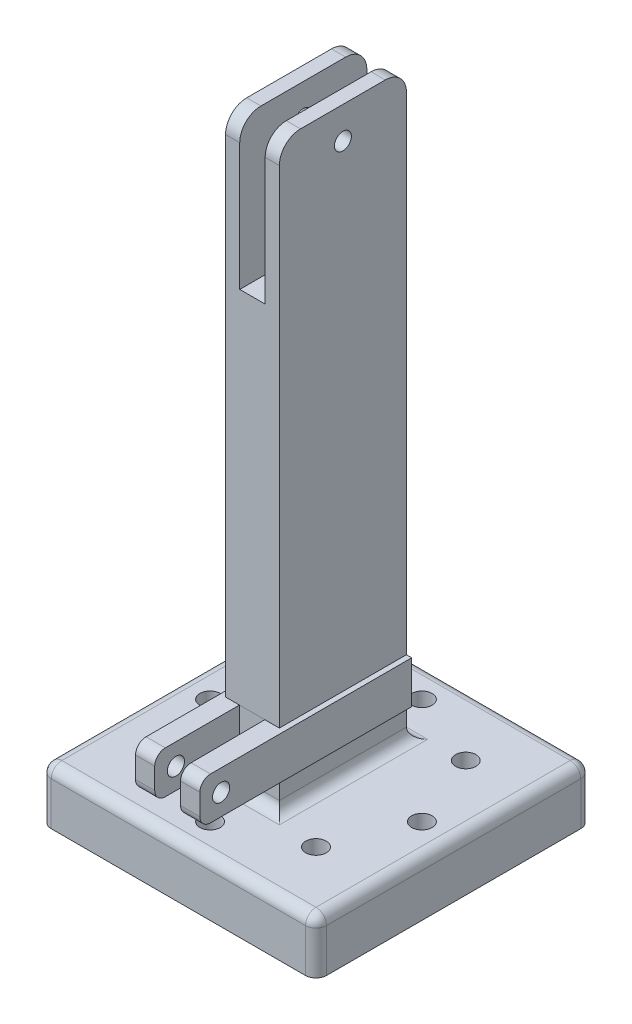
SolidWorks part; units mm, degrees
material "ABS P400"
ref_plane "Front Plane" through (0, 0, 0) normal (0, 0, 1) x (1, 0, 0)
ref_plane "Top Plane" through (0, 0, 0) normal (0, 1, 0) x (1, 0, 0)
ref_plane "Right Plane" through (0, 0, 0) normal (1, 0, 0) x (0, 0, -1)
sketch "Sketch1" plane through (0, 0, 0) normal (0, 1, 0) x (1, 0, 0)
  line L1 (32.5, -32.5) -> (-32.5, -32.5)
  line L2 (32.5, -32.5) -> (32.5, 32.5)
  line L3 (32.5, 32.5) -> (-32.5, 32.5)
  line L4 (-32.5, -32.5) -> (-32.5, 32.5)
  line L5 (32.5, -32.5) -> (-32.5, 32.5) construction
  line L6 (32.5, 32.5) -> (-32.5, -32.5) construction
  point P0 (0, 0)
  dimension "D1" = 65
extrude "Boss-Extrude1" add sketch "Sketch1" along normal blind 12.7
sketch "Sketch2" plane through (0, 0, 0) normal (1, 0, 0) x (0, 0, -1)
  line L0 (0, 0) -> (0, -27.9366) construction
  line L1 (-15, 0) -> (15, 0)
  line L3 (15, 0) -> (15, 145)
  line L4 (-10, 150) -> (10, 150)
  line L5 (-32.5, 0) -> (32.5, 0) construction
  line L6 (-15, 0) -> (-15, 145)
  arc A0 (15, 145) -> (10, 150) centre (10, 145) ccw
  arc A1 (-15, 145) -> (-10, 150) centre (-10, 145) cw
  circle A2 centre (0, 142.5) radius 2
  point P11 (15, 150)
  point P14 (-15, 150)
  dimension "D3" = 5
  dimension "D4" = 4
  dimension "D5" = 142.5
  dimension "D1" = 30
  dimension "D2" = 150
extrude "Boss-Extrude2" add sketch "Sketch2" along normal mid plane 12.7
fillet "Fillet1" radius 2.5 12 edges at (0, 12.7, -32.5) (32.5, 12.7, 0) (32.5, 6.35, -32.5) (32.5, 6.35, 32.5) (-32.5, 6.35, 32.5) (0, 12.7, 32.5) (-32.5, 6.35, -32.5) (-32.5, 12.7, 0) (0, 12.7, 15) (-6.35, 12.7, 0) (0, 12.7, -15) (6.35, 12.7, 0)
sketch "Sketch3" plane through (0, 0, 0) normal (0, 1, 0) x (1, 0, 0)
  line L0 (0, 158.75) -> (0, -158.75) construction
  line L1 (17.6777, 17.6777) -> (-17.6777, -17.6777) construction
  line L2 (17.6777, -17.6777) -> (-17.6777, 17.6777) construction
  circle A0 centre (0, 0) radius 25
  circle A1 centre (17.6777, -17.6777) radius 2.413
  circle A2 centre (25, 0) radius 2.413
  circle A3 centre (17.6777, 17.6777) radius 2.413
  circle A4 centre (0, 25) radius 2.413
  circle A5 centre (-17.6777, 17.6777) radius 2.413
  circle A6 centre (-25, 0) radius 2.413
  circle A7 centre (-17.6777, -17.6777) radius 2.413
  circle A8 centre (0, -25) radius 2.413
extrude "Cut-Extrude2" cut sketch "Sketch3" against normal blind 12.7 and the other way through all contours A0 A7 | A0 A7 | A0 A6 | A0 A6 | A0 A5 | A0 A5 | A0 A8 | A0 A8 | A0 A1 | A0 A1 | A0 A2 | A0 A2 | A0 A3 | A0 A3 | A0 A4 | A0 A4
sketch "Sketch4" plane through (0, 0, 0) normal (1, 0, 0) x (0, 0, -1)
  line L0 (15, 15.2) -> (15, 145) construction
  line L1 (15, 20) -> (-32.5, 20)
  line L2 (15, 20) -> (15, 30)
  line L3 (15, 30) -> (-32.5, 30)
  line L4 (-35, 22.5) -> (-35, 27.5)
  line L5 (-30, 0) -> (30, 0) construction
  circle A0 centre (-30, 25) radius 2.032
  arc A1 (-35, 22.5) -> (-32.5, 20) centre (-32.5, 22.5) ccw
  arc A2 (-35, 27.5) -> (-32.5, 30) centre (-32.5, 27.5) cw
  point P8 (15, 25)
  dimension "D1" = 4.064
  dimension "D4" = 45
  dimension "D5" = 25
  dimension "D6" = 2.5
  dimension "D2" = 10
  dimension "D3" = 50
extrude "Boss-Extrude4" add sketch "Sketch4" along normal mid plane 15.2 contours L2 L3 A2 L4 A1 L1 | A0
sketch "Sketch5" plane through (0, 30, 0) normal (0, 1, 0) x (1, 0, 0)
  line L1 (-3.0705, -14.9893) -> (-3.0705, -44.3845)
  line L2 (2.9295, -14.9893) -> (3.0705, -44.3845)
  line L3 (-3.0705, -44.3845) -> (3.0705, -44.3845)
  line L4 (0, -15) -> (3.0705, -44.3845) construction
  line L5 (0, -15) -> (-3.0705, -44.3845) construction
  line L6 (-3.0705, -14.9893) -> (2.9295, -14.9893)
  point P1 (0, -15)
  dimension "D1" = 6
  dimension "D2" = 29.3952
extrude "Cut-Extrude3" cut sketch "Sketch5" against normal blind 12.45
sketch "Sketch6" plane through (0, 0, 15) normal (0, 0, 1) x (1, 0, 0)
  line L0 (-3, 185) -> (3, 185)
  line L1 (-3, 185) -> (-3, 115)
  line L2 (3, 185) -> (3, 115)
  line L3 (-3, 115) -> (3, 115)
  line L4 (-3, 185) -> (3, 115) construction
  line L5 (3, 185) -> (-3, 115) construction
  line L6 (-3, 150) -> (3, 150)
  line L9 (6.35, 150) -> (-6.35, 150) construction
  point P1 (0, 150)
  line M8 (6.35, 145) -> (-6.35, 145)
  dimension "D1" = 35
  dimension "D2" = 6
extrude "Cut-Extrude4" cut sketch "Sketch6" against normal through all contours L1 L3 L2 M8 | L6 L1 L2 M8
